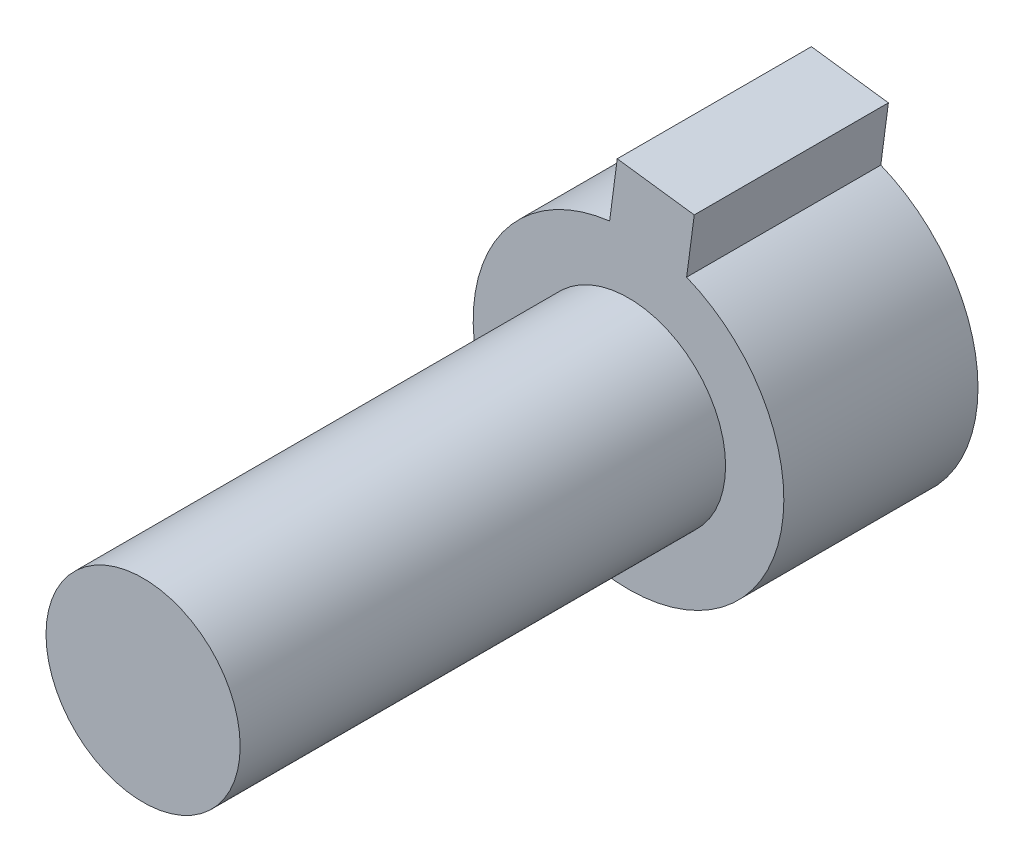
SolidWorks part; units mm, degrees
ref_plane "Front Plane" through (0, 0, 0) normal (0, 0, 1) x (1, 0, 0)
ref_plane "Top Plane" through (0, 0, 0) normal (0, 1, 0) x (1, 0, 0)
ref_plane "Right Plane" through (0, 0, 0) normal (1, 0, 0) x (0, 0, -1)
sketch "Sketch1" plane through (0, 0, 0) normal (0, 0, 1) x (1, 0, 0)
  line L1 (-0.5803, 10.9151) -> (3.3855, 10.393)
  line L2 (3.3855, 10.393) -> (2.9939, 7.4186)
  line L3 (-0.5803, 10.9151) -> (-0.9718, 7.9408)
  line L5 (0, -55) -> (0, 55) construction
  arc A0 (-0.9718, 7.9408) -> (2.9939, 7.4186) centre (0, 0) ccw
  dimension "D1" = 4
  dimension "D6" = 8
  dimension "D2" = 7.5
  dimension "D3" = 3
  dimension "D4" = 90
  dimension "D5" = 3
extrude "Boss-Extrude1" add sketch "Sketch1" along normal blind 10
sketch "Sketch2" plane through (0, 0, 10) normal (0, 0, 1) x (1, 0, 0)
  circle A0 centre (0, 0) radius 5
extrude "Boss-Extrude2" add sketch "Sketch2" along normal blind 25
